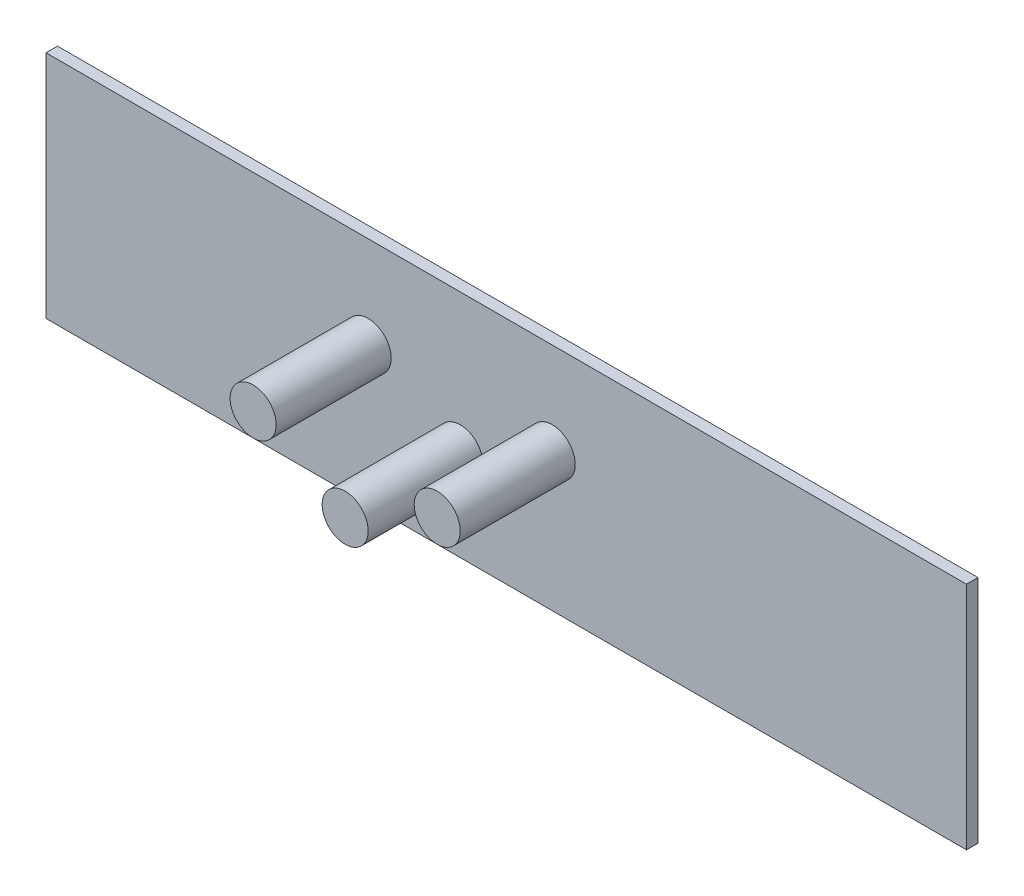
SolidWorks part; units mm, degrees
ref_plane "Front Plane" through (0, 0, 0) normal (0, 0, 1) x (1, 0, 0)
ref_plane "Top Plane" through (0, 0, 0) normal (0, 1, 0) x (1, 0, 0)
ref_plane "Right Plane" through (0, 0, 0) normal (1, 0, 0) x (0, 0, -1)
sketch "Sketch1" plane through (0, 0, 0) normal (0, 0, 1) x (1, 0, 0)
  line L1 (5000, 2500) -> (-15000, 2500)
  line L2 (5000, 2500) -> (5000, -2500)
  line L3 (5000, -2500) -> (-15000, -2500)
  line L4 (-15000, 2500) -> (-15000, -2500)
  line L5 (5000, 2500) -> (-15000, -2500) construction
  line L6 (5000, -2500) -> (-15000, 2500) construction
  point P0 (-5000, 0)
  dimension "D1" = 15000
  dimension "D2" = 5000
  dimension "D3" = 5000
extrude "Boss-Extrude1" add sketch "Sketch1" against normal blind 250
sketch "Sketch2" plane through (0, 0, 0) normal (0, 0, 1) x (1, 0, 0)
  line L0 (-15000, 0) -> (5000, 0) construction
  line L1 (-15000, 2500) -> (-15000, -2500) construction
  line L2 (5000, -2500) -> (5000, 2500) construction
  circle A0 centre (-8000, 500) radius 500
  circle A1 centre (-6000, -500) radius 500
  circle A2 centre (-4000, 500) radius 500
  point P12 (0, 0)
  point P14 (0, 0)
  dimension "D1" = 1000
  dimension "D2" = 1000
  dimension "D3" = 1000
  dimension "D4" = 500
  dimension "D5" = 8000
  dimension "D6" = 500
  dimension "D7" = 500
  dimension "D8" = 6000
  dimension "D9" = 4000
extrude "Boss-Extrude2" add sketch "Sketch2" along normal blind 2500
